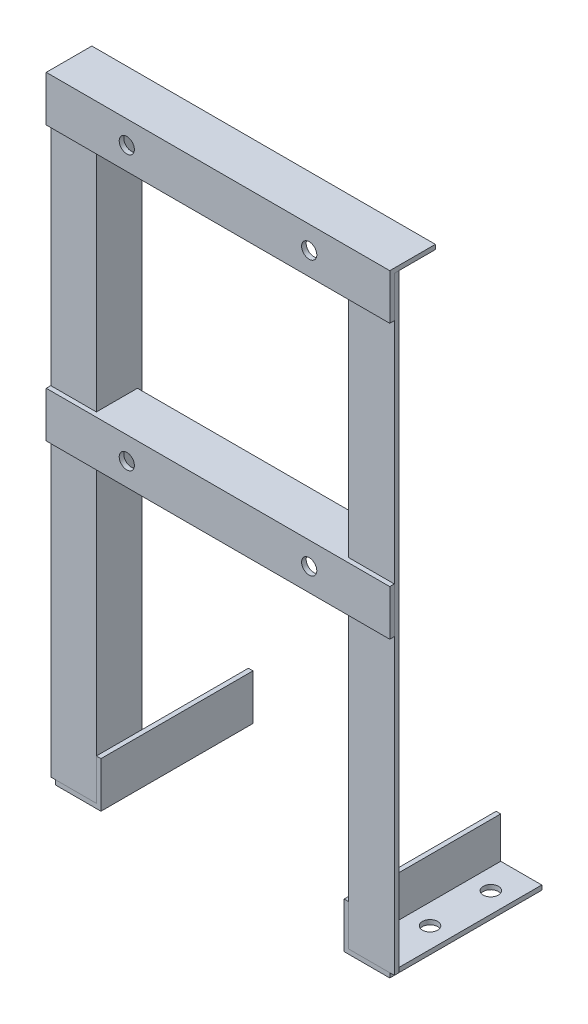
SolidWorks part; units mm, degrees
ref_plane "Front Plane" through (0, 0, 0) normal (0, 0, 1) x (1, 0, 0)
ref_plane "Top Plane" through (0, 0, 0) normal (0, 1, 0) x (1, 0, 0)
ref_plane "Right Plane" through (0, 0, 0) normal (1, 0, 0) x (0, 0, -1)
sketch "Sketch1" plane through (0, 0, 0) normal (0, 0, 1) x (1, 0, 0)
  line L0 (0, 219.7078) -> (0, 0) construction
  line L1 (-80, 30) -> (-80, 0)
  line L2 (-80, 0) -> (-110, 0)
  line L3 (-110, 0) -> (-110, 3)
  line L4 (-110, 3) -> (-83, 3)
  line L5 (-83, 3) -> (-83, 30)
  line L6 (-83, 30) -> (-80, 30)
  line L7 (83, 30) -> (80, 30)
  line L8 (83, 3) -> (83, 30)
  line L9 (110, 3) -> (83, 3)
  line L10 (110, 0) -> (110, 3)
  line L11 (80, 0) -> (110, 0)
  line L12 (80, 30) -> (80, 0)
  point P8 (-52.1933, 0)
  dimension "D1" = 30
  dimension "D2" = 3
  dimension "D3" = 80
extrude "Boss-Extrude1" add sketch "Sketch1" against normal blind 100
sketch "Sketch2" plane through (0, 0, 0) normal (0, 1, 0) x (1, 0, 0)
  line L0 (83, 30) -> (83, 0)
  line L1 (83, 0) -> (113, 0)
  line L2 (113, 0) -> (113, 3)
  line L3 (113, 3) -> (86, 3)
  line L4 (86, 3) -> (86, 30)
  line L5 (86, 30) -> (83, 30)
  line L6 (0, 75.9888) -> (0, 0) construction
  line L7 (-86, 30) -> (-83, 30)
  line L8 (-86, 3) -> (-86, 30)
  line L9 (-113, 3) -> (-86, 3)
  line L10 (-113, 0) -> (-113, 3)
  line L11 (-83, 0) -> (-113, 0)
  line L12 (-83, 30) -> (-83, 0)
  dimension "D1" = 30
  dimension "D2" = 3
extrude "Boss-Extrude2" add sketch "Sketch2" along normal blind 400 from surface at 3 separate body starting at face at (-96.5, 3, -50)
sketch "Sketch3" plane through (0, 0, 0) normal (1, 0, 0) x (0, 0, -1)
  line L0 (27, 406) -> (-3, 406)
  line L1 (-3, 406) -> (-3, 376)
  line L2 (-3, 376) -> (0, 376)
  line L3 (0, 376) -> (0, 403)
  line L4 (0, 403) -> (27, 403)
  line L5 (27, 403) -> (27, 406)
  line L6 (30, 403) -> (3, 403) construction
  line L7 (0, 403) -> (0, 3) construction
  dimension "D1" = 30
  dimension "D2" = 3
extrude "Boss-Extrude3" add sketch "Sketch3" along normal mid plane 226 separate body
sketch "Sketch4" plane through (0, 0, 0) normal (1, 0, 0) x (0, 0, -1)
  line L0 (0, 226) -> (0, 196)
  line L1 (0, 403) -> (0, 3) construction
  line L2 (0, 196) -> (-3, 196)
  line L3 (-3, 196) -> (-3, 226)
  line L4 (-3, 226) -> (0, 226)
  dimension "D1" = 3
  dimension "D2" = 30
  dimension "D3" = 150
extrude "Boss-Extrude4" add sketch "Sketch4" along normal mid plane 226 separate body
sketch "Sketch5" plane through (0, 0, 0) normal (1, 0, 0) x (0, 0, -1)
  line L0 (-3, 226) -> (27, 226)
  line L1 (27, 226) -> (27, 223)
  line L2 (27, 223) -> (-3, 223)
  line L3 (-3, 226) -> (-3, 196) construction
  line L4 (-3, 223) -> (-3, 226)
  dimension "D1" = 3
  dimension "D2" = 30
extrude "Boss-Extrude5" add sketch "Sketch5" against normal mid plane 166
sketch "Sketch6" plane through (0, 0, 3) normal (0, 0, 1) x (1, 0, 0)
  line L0 (-60, 391) -> (60, 391) construction
  line L1 (60, 391) -> (60, 211) construction
  line L2 (60, 211) -> (-60, 211) construction
  line L3 (-60, 211) -> (-60, 391) construction
  line L4 (0, 406) -> (0, 376) construction
  line L5 (113, 406) -> (-113, 406) construction
  line L6 (113, 376) -> (-113, 376) construction
  line L7 (0, 226) -> (0, 196) construction
  line L8 (-113, 226) -> (113, 226) construction
  line L9 (113, 196) -> (-113, 196) construction
  circle A0 centre (-60, 391) radius 5
  circle A1 centre (60, 391) radius 5
  circle A2 centre (-60, 211) radius 5
  circle A3 centre (60, 211) radius 5
  point P14 (0, 391)
  point P21 (0, 211)
  point P22 (0, 376)
  point P23 (0, 391)
  dimension "D2" = 10
  dimension "D1" = 120
extrude "Cut-Extrude1" cut sketch "Sketch6" against normal through all
sketch "Sketch7" plane through (0, 0, 0) normal (0, 1, 0) x (1, 0, 0)
  line L0 (-96.5, 80) -> (96.5, 80) construction
  line L1 (-96.5, 80) -> (-96.5, 40) construction
  line L2 (-96.5, 40) -> (96.5, 40) construction
  line L3 (96.5, 40) -> (96.5, 80) construction
  line L4 (-110, 63.5799) -> (-83, 63.5799) construction
  line L5 (-110, 100) -> (-110, 0) construction
  line L6 (-83, 100) -> (-83, 0) construction
  line L7 (110, 61.6568) -> (83, 61.6568) construction
  line L8 (110, 100) -> (110, 0) construction
  line L9 (83, 100) -> (83, 0) construction
  line L10 (110, 100) -> (83, 100) construction
  circle A0 centre (-96.5, 80) radius 5
  circle A1 centre (-96.5, 40) radius 5
  circle A2 centre (96.5, 80) radius 5
  circle A3 centre (96.5, 40) radius 5
  point P8 (0, 80)
  point P17 (-96.5, 63.5799)
  point P24 (96.5, 61.6568)
  point P27 (-116.5, 50)
  dimension "D3" = 10
  dimension "D1" = 20
  dimension "D2" = 40
extrude "Cut-Extrude2" cut sketch "Sketch7" along normal up to next (3 mm away)
